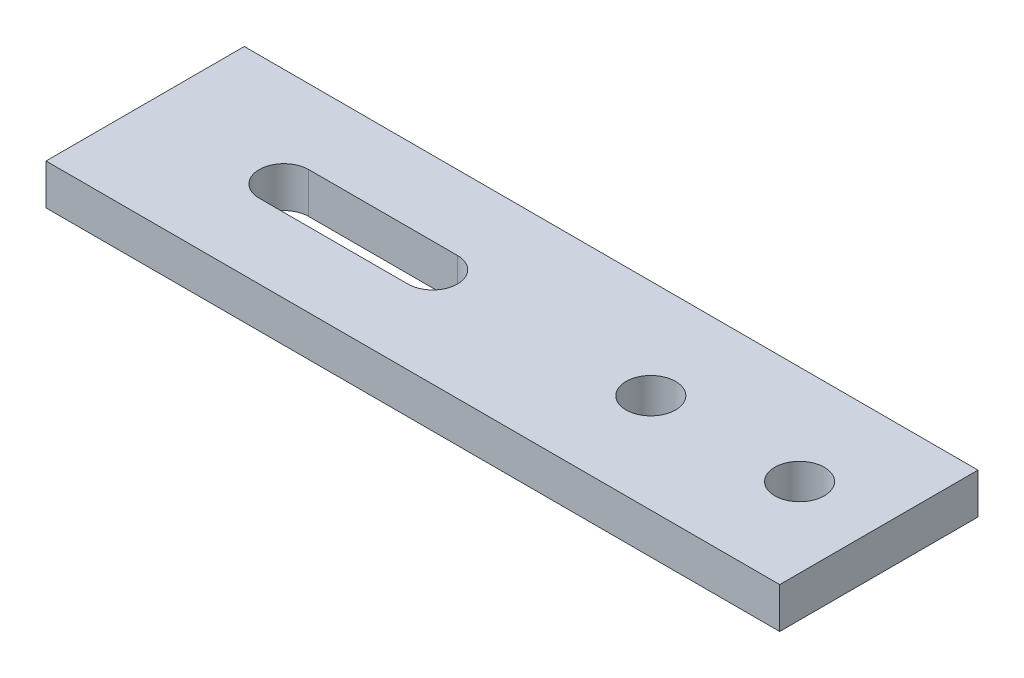
SolidWorks part; units mm, degrees
ref_plane "前视基准面" through (0, 0, 0) normal (0, 0, 1) x (1, 0, 0)
ref_plane "上视基准面" through (0, 0, 0) normal (0, 1, 0) x (1, 0, 0)
ref_plane "右视基准面" through (0, 0, 0) normal (1, 0, 0) x (0, 0, -1)
other "Configuration Table"
sketch "草图1" plane through (0, 0, 0) normal (0, 1, 0) x (1, 0, 0)
  line L1 (0, 0) -> (74, 0)
  line L2 (0, 0) -> (0, 20)
  line L3 (0, 20) -> (74, 20)
  line L4 (74, 0) -> (74, 20)
  dimension "D1" = 74
  dimension "D2" = 20
extrude "凸台-拉伸1" add sketch "草图1" along normal blind 4.1
sketch "草图2" plane through (0, 4.1, 0) normal (0, 1, 0) x (1, 0, 0)
  line L0 (74, 0) -> (74, 20) construction
  line L1 (74, 10) -> (0, 10) construction
  line L2 (0, 20) -> (0, 0) construction
  line L3 (14, 10) -> (29, 10) construction
  line L4 (14, 12.5) -> (29, 12.5)
  line L5 (14, 7.5) -> (29, 7.5)
  circle A0 centre (66, 10) radius 2.5
  circle A1 centre (51, 10) radius 2.5
  arc A2 (14, 12.5) -> (14, 7.5) centre (14, 10) ccw
  arc A3 (29, 7.5) -> (29, 12.5) centre (29, 10) ccw
  point P12 (21.5, 10)
  dimension "D1" = 5
  dimension "D4" = 2.5
  dimension "D2" = 8
  dimension "D3" = 15
  dimension "D5" = 15
  dimension "D6" = 14
extrude "切除-拉伸1" cut sketch "草图2" against normal blind 4.1
